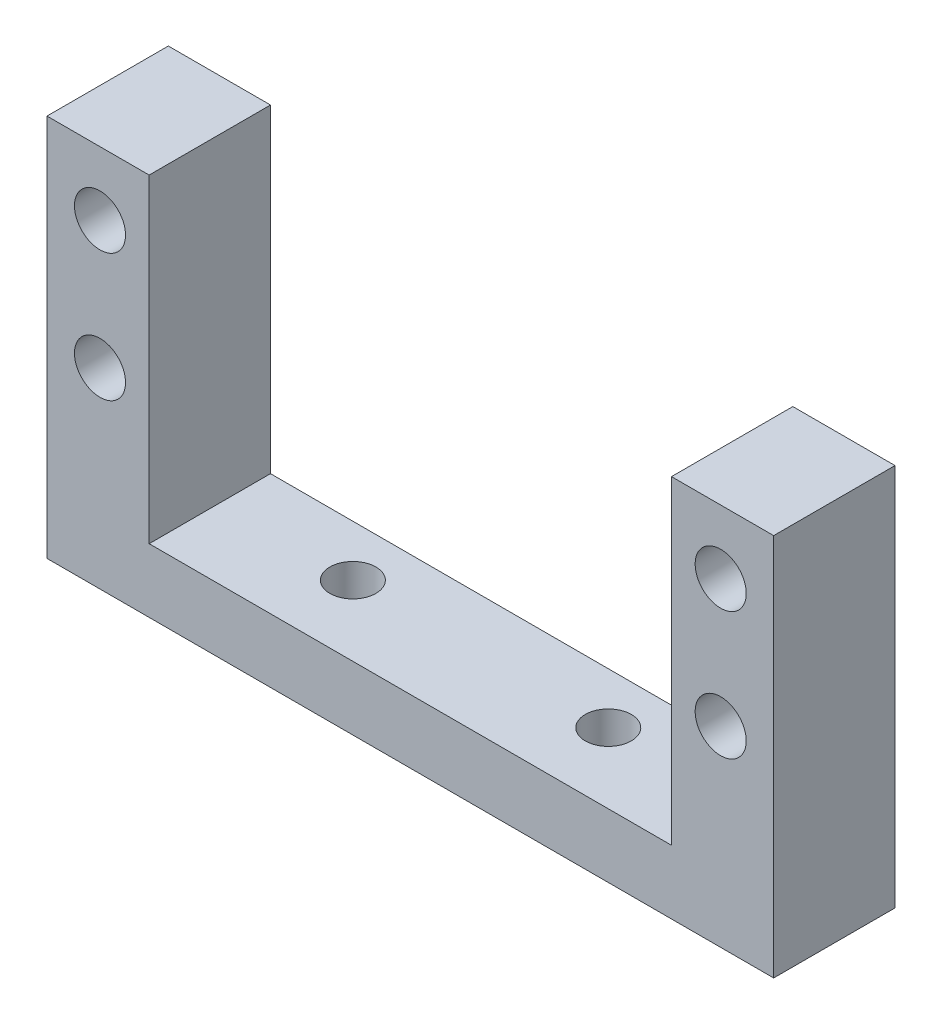
SolidWorks part; units mm, degrees
ref_plane "Plan de face" through (0, 0, 0) normal (0, 0, 1) x (1, 0, 0)
ref_plane "Plan de dessus" through (0, 0, 0) normal (0, 1, 0) x (1, 0, 0)
ref_plane "Plan de droite" through (0, 0, 0) normal (1, 0, 0) x (0, 0, -1)
sketch "Esquisse1" plane through (0, 0, 0) normal (0, 0, 1) x (1, 0, 0)
  line L0 (0, 0) -> (0, 30)
  line L1 (0, 0) -> (8, 0)
  line L2 (0, 30) -> (8, 30)
  line L3 (8, 0) -> (8, 30)
  line L5 (8, 0) -> (48.9, 0)
  line L6 (8, 5) -> (48.9, 5)
  line L8 (48.9, 0) -> (56.9, 0)
  line L9 (48.9, 0) -> (48.9, 30)
  line L10 (56.9, 0) -> (56.9, 30)
  line L11 (48.9, 30) -> (56.9, 30)
  line L12 (4.15, 30) -> (4.15, 0) construction
  line L14 (52.75, 0) -> (52.75, 30) construction
  circle A0 centre (4.15, 25) radius 2
  circle A1 centre (4.15, 15) radius 2
  circle A2 centre (52.75, 25) radius 2
  circle A3 centre (52.75, 15) radius 2
  dimension "D6" = 4
  dimension "D7" = 4
  dimension "D8" = 4
  dimension "D9" = 4
  dimension "D1" = 40.9
  dimension "D2" = 8
  dimension "D3" = 8
  dimension "D4" = 25
  dimension "D5" = 5
  dimension "D10" = 10
  dimension "D11" = 10
  dimension "D12" = 3.85
  dimension "D13" = 5
  dimension "D14" = 3.85
  dimension "D15" = 5
extrude "Boss.-Extru.1" add sketch "Esquisse1" along normal blind 11
sketch "Esquisse2" plane through (0, 0, 0) normal (0, -1, 0) x (1, 0, 0)
  line L0 (0, 4) -> (56.9, 4) construction
  line L3 (0, 11) -> (56.9, 11) construction
  line L5 (56.9, 11) -> (56.9, 0) construction
  line L6 (0, 11) -> (0, 0) construction
  circle A0 centre (18.45, 4) radius 1.8
  circle A1 centre (38.45, 4) radius 1.8
  point P12 (28.45, 4)
  dimension "D1" = 3.6
  dimension "D2" = 3.6
  dimension "D3" = 10
  dimension "D4" = 20
  dimension "D5" = 7
extrude "Enlèv. mat.-Extru.1" cut sketch "Esquisse2" against normal blind 9
sketch "Esquisse3" plane through (0, 0, 11) normal (0, 0, 1) x (1, 0, 0)
  line L0 (0, 30) -> (0, 0)
  line L1 (0, 30) -> (56.9, 30)
  line L2 (0, 0) -> (56.9, 0)
  line L3 (56.9, 30) -> (56.9, 0)
extrude "Enlèv. mat.-Extru.2" cut sketch "Esquisse3" against normal blind 1.5
